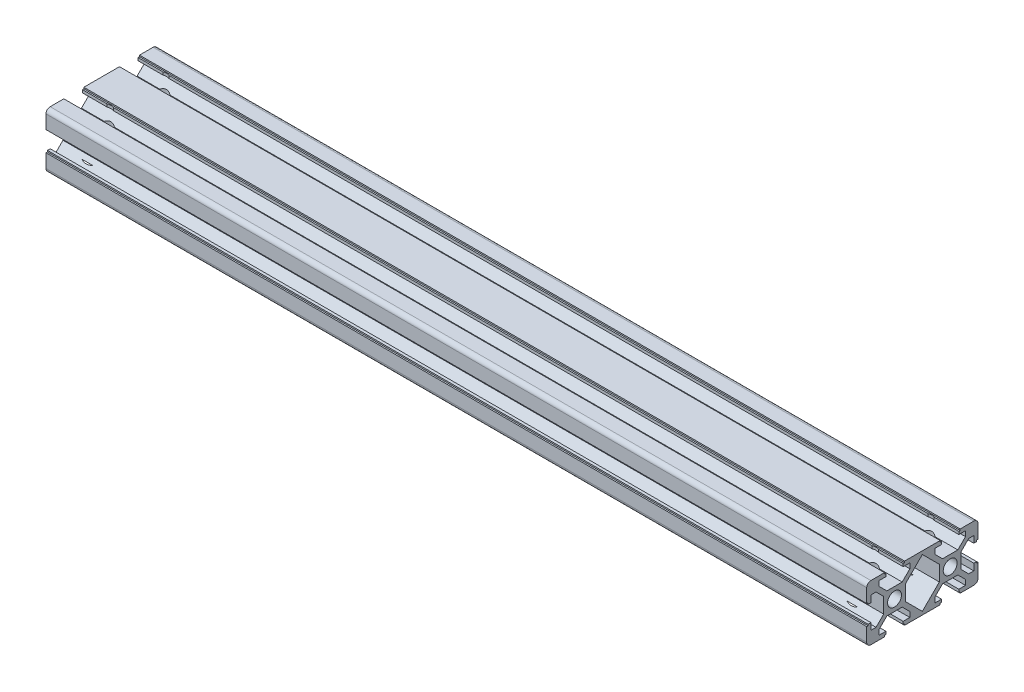
SolidWorks part; units mm, degrees
ref_plane "前视基准面" through (0, 0, 0) normal (0, 0, 1) x (1, 0, 0)
ref_plane "上视基准面" through (0, 0, 0) normal (0, 1, 0) x (1, 0, 0)
ref_plane "右视基准面" through (0, 0, 0) normal (1, 0, 0) x (0, 0, -1)
sketch "草图1" plane through (0, 0, 0) normal (0, 0, 1) x (1, 0, 0)
  line L0 (0, 0) -> (295, 0)
  dimension "D1" = 295
other "铝型材 20 X 40 X R1.5(1)"
ref_plane "基准面4" through (0, 0, 0) normal (1, 0, 0) x (0, 1, 0)
sketch "Sketch1" plane through (0, 0, 0) normal (1, 0, 0) x (0, 1, 0)
  line L0 (-3.6, 10) -> (-3.6, 9.5)
  line L1 (-3.6, 9.5) -> (-3.1, 9.5)
  line L2 (-3.1, 9.5) -> (-3.1, 8.5)
  line L3 (-3.1, 8.5) -> (-5.5, 8.5)
  line L4 (8.85, -10) -> (2.75, -3.9)
  line L5 (-10, -16.4) -> (-10, -3.6)
  line L6 (8.5, 10) -> (3.6, 10)
  line L7 (10, 8.5) -> (10, 3.6)
  line L8 (0, 14.8756) -> (0, 0) construction
  line L9 (0, 0) -> (10, 0) construction
  line L10 (-5.5, 8.5) -> (-5.5, 6.65)
  line L11 (-5.5, 6.65) -> (-2.75, 3.9)
  line L12 (-2.75, 3.9) -> (2.75, 3.9)
  line L13 (5.5, 6.65) -> (2.75, 3.9)
  line L14 (5.5, 8.5) -> (5.5, 6.65)
  line L15 (3.1, 8.5) -> (5.5, 8.5)
  line L16 (3.1, 9.5) -> (3.1, 8.5)
  line L17 (3.6, 9.5) -> (3.1, 9.5)
  line L18 (3.6, 10) -> (3.6, 9.5)
  line L19 (-3.6, 10) -> (-8.5, 10)
  line L20 (10, 3.6) -> (9.5, 3.6)
  line L21 (9.5, 3.6) -> (9.5, 3.1)
  line L22 (9.5, 3.1) -> (8.5, 3.1)
  line L23 (8.5, 3.1) -> (8.5, 5.5)
  line L24 (8.5, 5.5) -> (6.65, 5.5)
  line L25 (6.65, 5.5) -> (3.9, 2.75)
  line L26 (3.9, 2.75) -> (3.9, -2.75)
  line L27 (6.65, -5.5) -> (3.9, -2.75)
  line L28 (8.5, -5.5) -> (6.65, -5.5)
  line L29 (8.5, -3.1) -> (8.5, -5.5)
  line L30 (9.5, -3.1) -> (8.5, -3.1)
  line L31 (9.5, -3.6) -> (9.5, -3.1)
  line L32 (10, -3.6) -> (9.5, -3.6)
  line L33 (8.85, -10) -> (2.75, -16.1)
  line L34 (-8.85, -10) -> (-2.75, -16.1)
  line L35 (-8.85, -10) -> (-2.75, -3.9)
  line L39 (2.75, -3.9) -> (-2.75, -3.9)
  line L46 (-10, -3.6) -> (-9.5, -3.6)
  line L47 (-9.5, -3.6) -> (-9.5, -3.1)
  line L48 (-9.5, -3.1) -> (-8.5, -3.1)
  line L49 (-8.5, -3.1) -> (-8.5, -5.5)
  line L50 (-8.5, -5.5) -> (-6.65, -5.5)
  line L51 (-6.65, -5.5) -> (-3.9, -2.75)
  line L52 (-3.9, -2.75) -> (-3.9, 2.75)
  line L53 (-6.65, 5.5) -> (-3.9, 2.75)
  line L54 (-8.5, 5.5) -> (-6.65, 5.5)
  line L55 (-8.5, 3.1) -> (-8.5, 5.5)
  line L56 (-9.5, 3.1) -> (-8.5, 3.1)
  line L57 (-9.5, 3.6) -> (-9.5, 3.1)
  line L58 (-10, 3.6) -> (-9.5, 3.6)
  line L60 (-10, 3.6) -> (-10, 8.5)
  line L61 (10, -3.6) -> (10, -16.4)
  line L66 (-8.5, -30) -> (-3.6, -30)
  line L67 (-10, -28.5) -> (-10, -23.6)
  line L72 (-2.75, -16.1) -> (2.75, -16.1)
  line L80 (10, -16.4) -> (9.5, -16.4)
  line L81 (9.5, -16.4) -> (9.5, -16.9)
  line L82 (9.5, -16.9) -> (8.5, -16.9)
  line L83 (8.5, -16.9) -> (8.5, -14.5)
  line L84 (8.5, -14.5) -> (6.65, -14.5)
  line L85 (6.65, -14.5) -> (3.9, -17.25)
  line L86 (3.9, -17.25) -> (3.9, -22.75)
  line L87 (6.65, -25.5) -> (3.9, -22.75)
  line L88 (8.5, -25.5) -> (6.65, -25.5)
  line L89 (8.5, -23.1) -> (8.5, -25.5)
  line L90 (9.5, -23.1) -> (8.5, -23.1)
  line L91 (9.5, -23.6) -> (9.5, -23.1)
  line L92 (10, -23.6) -> (9.5, -23.6)
  line L93 (3.6, -30) -> (3.6, -29.5)
  line L94 (3.6, -29.5) -> (3.1, -29.5)
  line L95 (3.1, -29.5) -> (3.1, -28.5)
  line L96 (3.1, -28.5) -> (5.5, -28.5)
  line L97 (5.5, -28.5) -> (5.5, -26.65)
  line L98 (5.5, -26.65) -> (2.75, -23.9)
  line L99 (2.75, -23.9) -> (-2.75, -23.9)
  line L100 (-5.5, -26.65) -> (-2.75, -23.9)
  line L101 (-5.5, -28.5) -> (-5.5, -26.65)
  line L102 (-3.1, -28.5) -> (-5.5, -28.5)
  line L103 (-3.1, -29.5) -> (-3.1, -28.5)
  line L104 (-3.6, -29.5) -> (-3.1, -29.5)
  line L105 (-3.6, -30) -> (-3.6, -29.5)
  line L106 (-10, -23.6) -> (-9.5, -23.6)
  line L107 (-9.5, -23.6) -> (-9.5, -23.1)
  line L108 (-9.5, -23.1) -> (-8.5, -23.1)
  line L109 (-8.5, -23.1) -> (-8.5, -25.5)
  line L110 (-8.5, -25.5) -> (-6.65, -25.5)
  line L111 (-6.65, -25.5) -> (-3.9, -22.75)
  line L112 (-3.9, -22.75) -> (-3.9, -17.25)
  line L113 (-6.65, -14.5) -> (-3.9, -17.25)
  line L114 (-8.5, -14.5) -> (-6.65, -14.5)
  line L115 (-8.5, -16.9) -> (-8.5, -14.5)
  line L116 (-9.5, -16.9) -> (-8.5, -16.9)
  line L117 (-9.5, -16.4) -> (-9.5, -16.9)
  line L118 (-10, -16.4) -> (-9.5, -16.4)
  line L119 (3.6, -30) -> (8.5, -30)
  line L121 (10, -23.6) -> (10, -28.5)
  line L122 (0, -20) -> (10, -20) construction
  line L125 (3.6, -10) -> (3.6, -9.5) [skipped]
  line L127 (3.6, -9.5) -> (3.1, -9.5) [skipped]
  line L129 (3.1, -9.5) -> (3.1, -8.5) [skipped]
  line L131 (3.1, -8.5) -> (5.5, -8.5) [skipped]
  line L133 (-3.1, -8.5) -> (-5.5, -8.5) [skipped]
  line L135 (-3.1, -9.5) -> (-3.1, -8.5) [skipped]
  line L137 (-3.6, -9.5) -> (-3.1, -9.5) [skipped]
  line L139 (-3.6, -10) -> (-3.6, -9.5) [skipped]
  line L141 (-3.6, -10) -> (-3.6, -10.5) [skipped]
  line L142 (-3.6, -10.5) -> (-3.1, -10.5) [skipped]
  line L143 (-3.1, -10.5) -> (-3.1, -11.5) [skipped]
  line L144 (-3.1, -11.5) -> (-5.5, -11.5) [skipped]
  line L145 (8.5, -10) -> (3.6, -10) [skipped]
  line L146 (3.1, -11.5) -> (5.5, -11.5) [skipped]
  line L147 (3.1, -10.5) -> (3.1, -11.5) [skipped]
  line L148 (3.6, -10.5) -> (3.1, -10.5) [skipped]
  line L149 (3.6, -10) -> (3.6, -10.5) [skipped]
  line L150 (-3.6, -10) -> (-8.5, -10) [skipped]
  line L151 (-10, -16.4) -> (-10, -11.5) [skipped]
  line L152 (10, -11.5) -> (10, -16.4) [skipped]
  line L154 (-5.5, -8.5) -> (-5.5, -6.65) [skipped]
  line L156 (5.5, -8.5) -> (5.5, -6.65) [skipped]
  line L157 (5.5, -11.5) -> (5.5, -13.35) [skipped]
  line L158 (-5.5, -11.5) -> (-5.5, -13.35) [skipped]
  line L160 (-12.2446, -13.3946) -> (-10, -11.15) [skipped]
  line L161 (13.644, -5.206) -> (10, -8.85) [skipped]
  line L163 (12.1963, -13.3463) -> (10, -11.15) [skipped]
  line L164 (-11.1344, -7.7156) -> (-10, -8.85) [skipped]
  circle A0 centre (0, 0) radius 2.5
  arc A1 (-10, 8.5) -> (-8.5, 10) centre (-8.5, 8.5) cw
  arc A2 (10, 8.5) -> (8.5, 10) centre (8.5, 8.5) ccw
  arc A3 (10, -28.5) -> (8.5, -30) centre (8.5, -28.5) cw
  arc A4 (-10, -28.5) -> (-8.5, -30) centre (-8.5, -28.5) ccw
  circle A5 centre (0, -20) radius 2.5
  arc A12 (-10, -11.5) -> (-8.5, -10) centre (-8.5, -11.5) cw [skipped]
  arc A13 (10, -11.5) -> (8.5, -10) centre (8.5, -11.5) ccw [skipped]
  point P0 (-10, 0)
  point P1 (10, 0)
  point P2 (0, 10)
  point P4 (0, 0)
  point P5 (0, -10)
  point P6 (-10, -10)
  point P7 (10, 10)
  point P8 (-10, 10)
  point P12 (-10, -10)
  point P13 (10, -10)
  point P15 (0, -10)
  point P16 (10, -10)
  point P36 (-10, 10)
  point P39 (10, 10)
  point P43 (-10, -20)
  point P44 (10, -20)
  point P62 (0, 0)
  point P88 (0, -30)
  point P89 (0, -20)
  point P90 (-10, -30)
  point P91 (10, -30)
  dimension "D1" = 11
  dimension "D2" = 20
  dimension "D3" = 6.2
  dimension "D4" = 7.2
  dimension "D5" = 6.1
  dimension "D6" = 5
  dimension "D7" = 1.5
  dimension "D8" = 45
  dimension "D14" = 20
  dimension "D15" = 1.5
  dimension "D9" = 0.5
  dimension "D10" = 1
  dimension "D11" = 5.5
  dimension "D12" = 10
  dimension "D13" = 40
  dimension "D16" = 45
  dimension "D17" = 45
  dimension "D18" = 45
  dimension "D19" = 6.2
sketch "草图7" plane through (0, 0, 10) normal (0, 0, 1) x (1, 0, 0)
  line L0 (295, 8.5) -> (295, 3.6) construction
  line L1 (295, -3.6) -> (295, -8.5) construction
  line L2 (0, 8.5) -> (0, 3.6) construction
  line L3 (0, -3.6) -> (0, -8.5) construction
  point P0 (10, 6.05)
  point P2 (10, -6.05)
  point P4 (285, 6.05)
  point P6 (285, -6.05)
  point P17 (0, -6.05)
  dimension "D1" = 10
  dimension "D2" = 10
  dimension "D3" = 10
  dimension "D4" = 10
sketch "草图9" plane through (0, -10, 0) normal (0, -1, 0) x (1, 0, 0)
  line L0 (2.2484, 0) -> (36.7099, 0) construction
  line L2 (3.9291, -20) -> (41.9569, -20) construction
  line L3 (295, 2.75) -> (295, -2.75) construction
  line L4 (295, -17.25) -> (295, -22.75) construction
  line L5 (0, 2.75) -> (0, -2.75) construction
  line L6 (0, -17.25) -> (0, -22.75) construction
  point P8 (10, 0)
  point P10 (10, -20)
  point P12 (285, 0)
  point P14 (285, -20)
  dimension "D1" = 10
  dimension "D2" = 10
  dimension "D3" = 10
  dimension "D4" = 10
hole_wizard "M6 六角凹头盖的柱孔1" positions "草图9" profile "草图10" counterbore size "M6" standard "BSI" end condition through all
sketch "草图10" plane through (285, -10, -20) normal (1, 0, 0) x (0, 0, -1)
  line L0 (0, 0) -> (0, 20)
  line L1 (0, 20) -> (3.3, 20)
  line L3 (3.3, 20) -> (3.3, 6)
  line L4 (3.3, 6) -> (5.5, 6)
  line L5 (5.5, 6) -> (5.5, 0)
  line L7 (5.5, 0) -> (0, 0)
  line L11 (0, -6.35) -> (0, 107.95) construction
  dimension "通孔孔直径" = 6.6
  dimension "通孔孔深度" = 20
  dimension "柱形沉头孔直径" = 11
  dimension "柱形沉头孔深度" = 6
